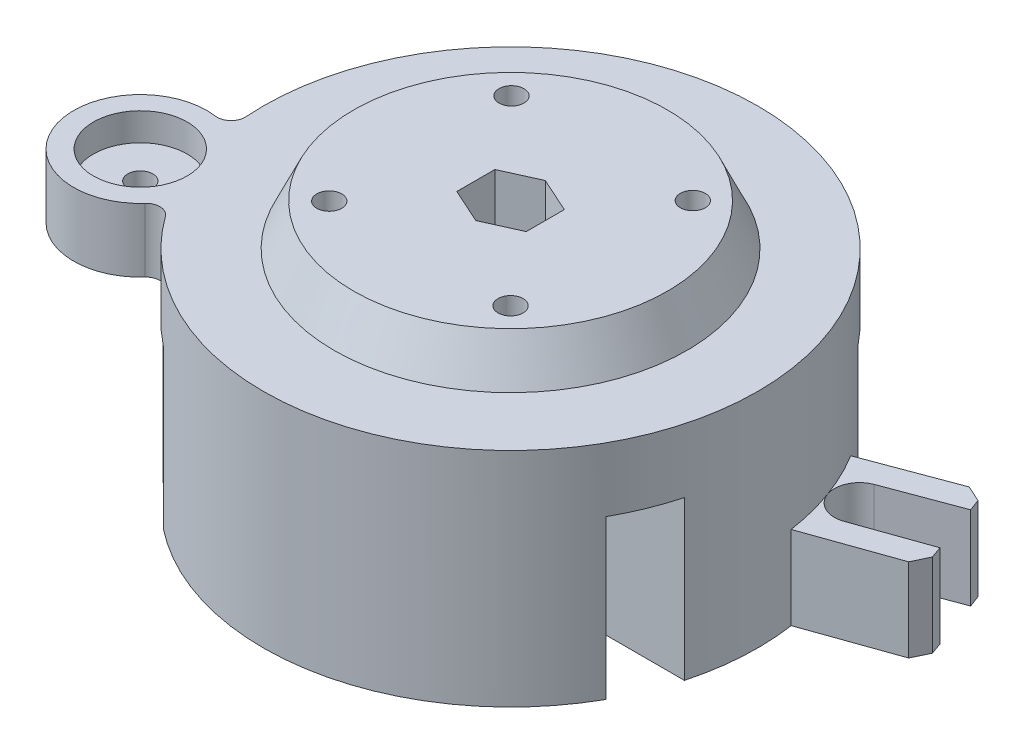
SolidWorks part; units mm, degrees
ref_plane "Front Plane" through (0, 0, 0) normal (0, 0, 1) x (1, 0, 0)
ref_plane "Top Plane" through (0, 0, 0) normal (0, 1, 0) x (1, 0, 0)
ref_plane "Right Plane" through (0, 0, 0) normal (1, 0, 0) x (0, 0, -1)
sketch "Sketch2" plane through (0, 0, 0) normal (0, 1, 0) x (1, 0, 0)
  line L0 (-400.5493, 0) -> (19626.9166, 0) construction
  line L1 (0, -400.5493) -> (0, 19626.9166) construction
  line L2 (0, 6.35) -> (6.35, 3.4835)
  line L9 (6.35, 3.4835) -> (6.35, -3.4835)
  line L10 (6.35, -3.4835) -> (0, -6.35)
  line L12 (-6.35, -3.4835) -> (0, -6.35)
  line L13 (-6.35, 3.4835) -> (-6.35, -3.4835)
  line L14 (0, 6.35) -> (-6.35, 3.4835)
  circle A0 centre (0, 0) radius 32.258
  circle A1 centre (0, 0) radius 45.212
  point P7 (6.35, 0)
  point P21 (-16.6624, 16.6624)
  point P22 (7.8107, 16.6624)
  point P23 (16.6624, -16.6624)
  point P24 (-16.6624, -16.6624)
  dimension "D1" = 12.7
  dimension "D4" = 64.516
  dimension "D5" = 90.424
  dimension "D2" = 131.41
  dimension "D3" = 12.7
extrude "Boss-Extrude3" add sketch "Sketch2" against normal blind 40.64 contours A1 A0 | A0 L14 L2 L9 L10 L12 L13
sketch "Sketch4" plane through (0, 0, 0) normal (0, 1, 0) x (1, 0, 0)
  circle A0 centre (0, 0) radius 32.258
  dimension "D1" = 64.516
extrude "Boss-Extrude4" add sketch "Sketch4" along normal blind 7.62 draft 25
sketch "Sketch6" plane through (0, -40.64, 0) normal (0, -1, 0) x (-1, 0, 0)
  line L0 (6.35, -3.4835) -> (0, -6.35)
  line L1 (0, -6.35) -> (-6.35, -3.4835)
  line L2 (-6.35, -3.4835) -> (-6.35, 3.4835)
  line L3 (-6.35, 3.4835) -> (0, 6.35)
  line L4 (0, 6.35) -> (6.35, 3.4835)
  line L5 (6.35, 3.4835) -> (6.35, -3.4835)
extrude "Cut-Extrude1" cut sketch "Sketch6" against normal through all
sketch "Sketch7" plane through (0, 7.62, 0) normal (0, 1, 0) x (1, 0, 0)
  line L0 (0, -1000) -> (0, 49000) construction
  line L2 (-1000, 0) -> (49000, 0) construction
  circle A0 centre (-16.4952, 16.6624) radius 2.286
  circle A1 centre (16.6624, 16.6624) radius 2.286
  circle A3 centre (16.6624, -16.6624) radius 2.286
  circle A4 centre (-16.4952, -16.6624) radius 2.286
  point P10 (16.6624, 16.6624)
  point P11 (-16.4952, 16.6624)
  point P12 (16.6624, -16.6624)
  point P13 (-16.4952, -16.6624)
  dimension "D1" = 4.572
  dimension "D2" = 4.572
  dimension "D3" = 4.572
  dimension "D4" = 4.572
extrude "Cut-Extrude2" cut sketch "Sketch7" against normal through all
sketch "Sketch12" plane through (0, 7.62, 0) normal (0, 1, 0) x (1, 0, 0)
  line L0 (0, 0) -> (50000, 0) construction
  line L1 (0, 0) -> (-46984.631, -17101.0072) construction
  circle A0 centre (-49.6458, -18.0696) radius 4.0442
  arc A2 (-47.9736, -5.9928) -> (-40.6021, -26.2461) centre (-49.6458, -18.0696) ccw
  arc A3 (45.212, 0) -> (42.4854, 15.4634) centre (0, 0) ccw
  arc A4 (-36.6585, -26.4628) -> (-40.6021, -26.2461) centre (-38.7179, -27.9495) ccw
  arc A5 (-45.092, -3.2919) -> (-47.9736, -5.9928) centre (-47.6253, -3.4768) cw
  arc A6 (-36.6585, -26.4628) -> (-45.092, -3.2919) centre (0, 0) cw
  arc A7 (-45.212, 0) -> (-45.092, -3.2919) centre (0, 0) ccw
  dimension "D2" = 2.54
  dimension "D1" = 20
  dimension "D3" = 52.832
extrude "Boss-Extrude8" add sketch "Sketch12" against normal blind 11.684 from surface at -7.62 contours A4 A6 A5 A2 A0
sketch "Sketch16" plane through (0, 0, 0) normal (0, 1, 0) x (1, 0, 0)
  circle A0 centre (-49.6458, -18.0696) radius 3.175
sketch "Sketch18" plane through (0, 0, 0) normal (0, 1, 0) x (1, 0, 0)
  circle A1 centre (-49.6458, -18.0696) radius 8.5673
  dimension "D1" = 17.1345
extrude "Cut-Extrude3" cut sketch "Sketch18" against normal blind 5.08
sketch "Sketch19" plane through (0, -5.08, 0) normal (0, 1, 0) x (1, 0, 0)
  circle A1 centre (-49.6458, -18.0696) radius 2.286
  dimension "D1" = 4.572
extrude "Cut-Extrude4" cut sketch "Sketch19" against normal through all
sketch "Sketch20" plane through (0, -40.64, 0) normal (0, -1, 0) x (1, 0, 0)
  line L0 (-5.0709, 1.8457) -> (-46989.7019, 17102.8528) construction
  line L1 (48.3078, -12.7174) -> (61.2371, -17.2959)
  line L2 (61.2371, -17.2959) -> (62.0002, -15.141)
  line L3 (62.0002, -15.141) -> (60.6019, -12.2094)
  line L4 (60.6019, -12.2094) -> (44.7293, -6.5887)
  line L5 (45.1805, -21.3096) -> (58.0279, -26.113)
  line L6 (58.0279, -26.113) -> (57.2273, -28.2543)
  line L7 (57.2273, -28.2543) -> (54.2718, -29.6012)
  line L8 (54.2718, -29.6012) -> (38.4998, -23.7043)
  arc A0 (48.3078, -12.7174) -> (45.1805, -21.3096) centre (46.7817, -17.0271) ccw
  circle A1 centre (0, 0) radius 45.212 construction
  arc A2 (38.4998, -23.7043) -> (44.7293, -6.5887) centre (0, 0) ccw
  circle M5 centre (0, 0) radius 45.212
  dimension "D1" = 4.572
  dimension "D3" = 13.716
  dimension "D2" = 49.784
  dimension "D4" = 1
  dimension "D5" = 45
extrude "Boss-Extrude9" add sketch "Sketch20" against normal blind 15.24 contours A0 L1 L2 L3 L4 M5 | A0 L8 L7 L6 L5 M5
sketch "Sketch21" plane through (0, -40.64, 0) normal (0, -1, 0) x (1, 0, 0)
  line L0 (16.6624, 6.5024) -> (26.8224, 6.5024)
  line L1 (16.6624, -983.3376) -> (16.6624, 49016.6624) construction
  line L2 (26.8224, 6.5024) -> (26.8224, 11.8441)
  line L3 (26.8224, 11.8441) -> (43.633, 11.8441)
  line L4 (16.6624, 26.8224) -> (25.3049, 26.8224)
  line L5 (25.3049, 26.8224) -> (25.3049, 22.0041)
  line L6 (25.3049, 22.0041) -> (39.4962, 22.0041)
  line L7 (-16.4952, 16.6624) -> (-35371.8343, -35338.6767) construction
  line L8 (-23.6794, 9.4782) -> (-30.8636, 16.6624)
  line L9 (-30.8636, 16.6624) -> (-27.2715, 20.2545)
  line L10 (-27.2715, 20.2545) -> (-35.2851, 28.2681)
  line L11 (-9.311, 23.8466) -> (-16.4952, 31.0308)
  line L12 (-16.4952, 31.0308) -> (-20.0873, 27.4387)
  line L13 (-20.0873, 27.4387) -> (-28.082, 35.4334)
  arc A0 (-23.6794, 9.4782) -> (-9.311, 23.8466) centre (-16.4952, 16.6624) ccw
  arc A1 (16.6624, 26.8224) -> (16.6624, 6.5024) centre (16.6624, 16.6624) ccw
  arc A2 (-45.092, 3.2919) -> (-36.6585, 26.4628) centre (0, 0) ccw construction
  arc A3 (43.633, 11.8441) -> (39.4962, 22.0041) centre (0, 0) ccw
  arc A4 (-28.082, 35.4334) -> (-35.2851, 28.2681) centre (0, 0) ccw
  arc A5 (14.6222, 42.7822) -> (10.7562, 43.9139) centre (0, 0) ccw
  point P4 (26.8224, 9.1732)
  circle M1 centre (-16.4952, 16.6624) radius 2.286
  circle M2 centre (16.6624, 16.6624) radius 2.286
  arc M5 (44.7293, -6.5887) -> (38.4998, -23.7043) centre (0, 0) ccw
  dimension "D1" = 10.16
  dimension "D2" = 10.16
  dimension "D6" = 10.16
  dimension "D3" = 10.16
  dimension "D4" = 8.6425
  dimension "D5" = 10.16
  dimension "D7" = 10.16
extrude "Cut-Extrude5" cut sketch "Sketch21" against normal blind 28.956 contours L8 A0 L11 L12 L13 L10 L9 M5 M1 | L4 A1 L0 L2 L3 L6 L5 M5 M2
pattern_circular "CirPattern1" count 2 over 360 about axis through (0, 0, 0) along (0, 1, 0) of "Cut-Extrude5"
